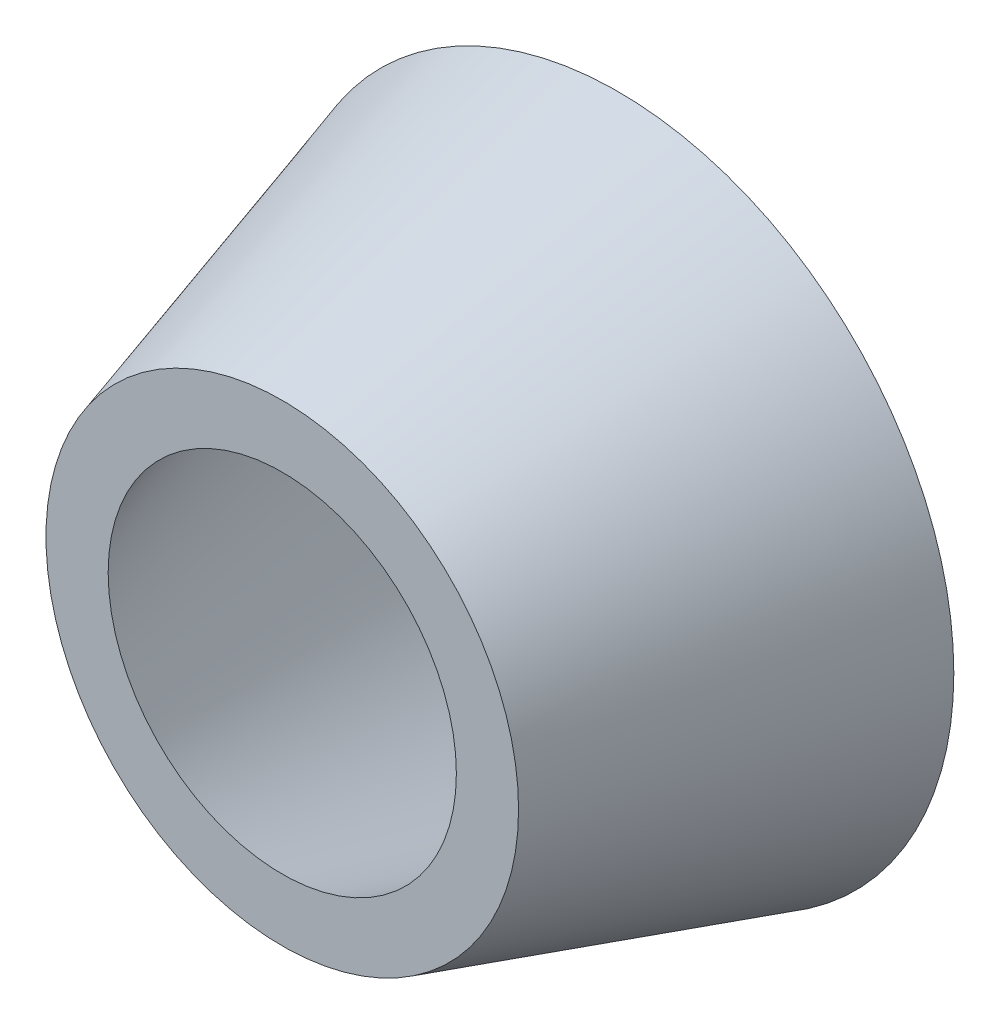
SolidWorks part; units mm, degrees
ref_plane "Спереди" through (0, 0, 0) normal (0, 0, 1) x (1, 0, 0)
ref_plane "Сверху" through (0, 0, 0) normal (0, 1, 0) x (1, 0, 0)
ref_plane "Справа" through (0, 0, 0) normal (1, 0, 0) x (0, 0, -1)
sketch "Эскиз1" plane through (0, 0, 0) normal (1, 0, 0) x (0, 0, -1)
  line L0 (0, 14) -> (27, 22)
  line L1 (27, 22) -> (27, 27)
  line L2 (27, 27) -> (0, 19)
  line L3 (0, 19) -> (0, 14)
  line L4 (-28.2135, 0) -> (44.2086, 0) construction
  dimension "D1" = 19
  dimension "D2" = 14
  dimension "D3" = 27
  dimension "D4" = 27
  dimension "D5" = 22
revolve "Повернуть1" add sketch "Эскиз1" angle 360 about L4
